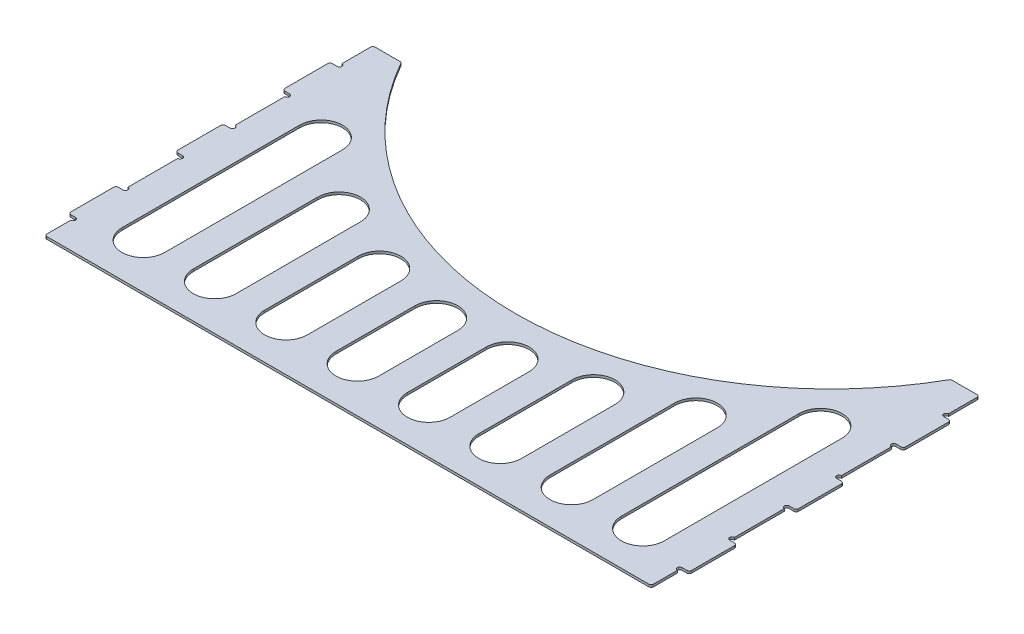
SolidWorks part; units mm, degrees
material "Thornel Mat VMA"
ref_plane "前视基准面" through (0, 0, 0) normal (0, 0, 1) x (1, 0, 0)
ref_plane "上视基准面" through (0, 0, 0) normal (0, 1, 0) x (1, 0, 0)
ref_plane "右视基准面" through (0, 0, 0) normal (1, 0, 0) x (0, 0, -1)
sketch "草图1" plane through (0, 0, 0) normal (0, 1, 0) x (1, 0, 0)
  line L1 (-127.5, -138) -> (127.5, -138)
  line L9 (-127.5, -138) -> (-127.5, 0)
  line L10 (-127.5, 0) -> (127.5, 0)
  line L13 (0, -0.55) -> (0, 0.55) construction
  line L14 (127.5, -138) -> (127.5, 0)
  dimension "D3" = 255
  dimension "D5" = 138
extrude "凸台-拉伸1" add sketch "草图1" along normal blind 1
sketch "草图2" plane through (0, 1, 0) normal (0, 1, 0) x (1, 0, 0)
  line L0 (127.5, 0) -> (-127.5, 0) construction
  line L1 (-115.5, 0) -> (115.5, 0)
  line L2 (-127.5, 0) -> (-127.5, -138) construction
  line L3 (127.5, -138) -> (127.5, 0) construction
  arc A0 (-115.5, 0) -> (115.5, 0) centre (0, 65) ccw
  dimension "D1" = 12
  dimension "D2" = 12
  dimension "D3" = 65
extrude "切除-拉伸1" cut sketch "草图2" against normal through all
sketch "草图5" plane through (0, 1, 0) normal (0, 1, 0) x (1, 0, 0)
  line L0 (-115.5, 0) -> (-127.5, 0) construction
  line L1 (-127.5, -15) -> (-130.5, -15)
  line L2 (-127.5, -15) -> (-127.5, -35)
  line L3 (-127.5, -35) -> (-130.5, -35)
  line L4 (-130.5, -15) -> (-130.5, -35)
  line L5 (-127.5, -60) -> (-130.5, -60)
  line L6 (0, -0.55) -> (0, 0.55) construction
  line L7 (127.5, -35) -> (130.5, -35)
  line L8 (130.5, -15) -> (130.5, -35)
  line L9 (127.5, -15) -> (130.5, -15)
  line L10 (127.5, -15) -> (127.5, -35)
  line L11 (-127.5, 0) -> (-127.5, -138) construction
  line L12 (-127.5, -60) -> (-127.5, -80)
  line L13 (-127.5, -80) -> (-130.5, -80)
  line L14 (-130.5, -60) -> (-130.5, -80)
  line L15 (-127.5, -105) -> (-130.5, -105)
  line L16 (-127.5, -105) -> (-127.5, -125)
  line L17 (-127.5, -125) -> (-130.5, -125)
  line L18 (-130.5, -105) -> (-130.5, -125)
  line L19 (-127.5, 0) -> (-127.5, -138) construction
  line L20 (130.5, -105) -> (130.5, -125)
  line L21 (127.5, -125) -> (130.5, -125)
  line L22 (127.5, -105) -> (127.5, -125)
  line L23 (127.5, -105) -> (130.5, -105)
  line L24 (130.5, -60) -> (130.5, -80)
  line L25 (127.5, -80) -> (130.5, -80)
  line L26 (127.5, -60) -> (127.5, -80)
  line L27 (127.5, -60) -> (130.5, -60)
  dimension "D1" = 3
  dimension "D2" = 20
  dimension "D3" = 15
  dimension "D5" = 25
  dimension "D4" = 3
extrude "凸台-拉伸3" add sketch "草图5" against normal blind 1
sketch "草图6" plane through (0, 1, 0) normal (0, 1, 0) x (1, 0, 0)
  line L0 (-127.5, -35) -> (-127.5, -60) construction
  line L1 (-127.5, -80) -> (-127.5, -105) construction
  line L2 (0, -0.55) -> (0, 0.55) construction
  line L3 (-127.5, 0) -> (-127.5, -15) construction
  line L4 (-127.5, -35) -> (-127.5, -60) construction
  line L5 (-127.5, -125) -> (-127.5, -138) construction
  circle A0 centre (-127.5, -14) radius 1
  circle A1 centre (-127.5, -36) radius 1
  circle A2 centre (127.5, -36) radius 1
  circle A3 centre (127.5, -14) radius 1
  circle A4 centre (-127.5, -59) radius 1
  circle A5 centre (-127.5, -81) radius 1
  circle A6 centre (-127.5, -104) radius 1
  circle A7 centre (-127.5, -126) radius 1
  circle A8 centre (127.5, -126) radius 1
  circle A9 centre (127.5, -104) radius 1
  circle A10 centre (127.5, -81) radius 1
  circle A11 centre (127.5, -59) radius 1
  dimension "D1" = 2
extrude "切除-拉伸3" cut sketch "草图6" against normal through all
sketch "草图7" plane through (0, 1, 0) normal (0, 1, 0) x (1, 0, 0)
  line L0 (-105, -119) -> (-15, -119) construction
  line L3 (-127.5, -138) -> (127.5, -138) construction
  line L9 (-105, -44.2591) -> (-105, -119) construction
  line L10 (-96, -44.2591) -> (-96, -119)
  line L11 (-114, -44.2591) -> (-114, -119)
  line L12 (-75, -66.6721) -> (-75, -119) construction
  line L13 (-66, -66.6721) -> (-66, -119)
  line L14 (-84, -66.6721) -> (-84, -119)
  line L15 (-45, -79.6981) -> (-45, -119) construction
  line L16 (-36, -79.6981) -> (-36, -119)
  line L17 (-54, -79.6981) -> (-54, -119)
  line L260 (-15, -85.7897) -> (-15, -119) construction
  line L261 (-6, -85.7897) -> (-6, -119)
  line L262 (-24, -85.7897) -> (-24, -119)
  line L263 (0, -0.55) -> (0, 0.55) construction
  line L264 (15, -85.7897) -> (15, -119) construction
  line L265 (6, -85.7897) -> (6, -119)
  line L266 (24, -85.7897) -> (24, -119)
  line L289 (45, -79.6981) -> (45, -119) construction
  line L290 (36, -79.6981) -> (36, -119)
  line L291 (54, -79.6981) -> (54, -119)
  line L292 (75, -66.6721) -> (75, -119) construction
  line L293 (66, -66.6721) -> (66, -119)
  line L294 (84, -66.6721) -> (84, -119)
  line L295 (105, -44.2591) -> (105, -119) construction
  line L296 (96, -44.2591) -> (96, -119)
  line L297 (114, -44.2591) -> (114, -119)
  arc A6 (-96, -44.2591) -> (-114, -44.2591) centre (-105, -44.2591) ccw
  arc A7 (-114, -119) -> (-96, -119) centre (-105, -119) ccw
  arc A8 (-66, -66.6721) -> (-84, -66.6721) centre (-75, -66.6721) ccw
  arc A9 (-84, -119) -> (-66, -119) centre (-75, -119) ccw
  arc A10 (-36, -79.6981) -> (-54, -79.6981) centre (-45, -79.6981) ccw
  arc A11 (-54, -119) -> (-36, -119) centre (-45, -119) ccw
  arc A14 (-124.2147, -4.9044) -> (124.2147, -4.9044) centre (0, 65) ccw
  circle A15 centre (0, 65) radius 142.534 construction
  arc A168 (-6, -85.7897) -> (-24, -85.7897) centre (-15, -85.7897) ccw
  arc A171 (-24, -119) -> (-6, -119) centre (-15, -119) ccw
  arc A172 (6, -85.7897) -> (24, -85.7897) centre (15, -85.7897) cw
  arc A173 (24, -119) -> (6, -119) centre (15, -119) cw
  arc A174 (36, -79.6981) -> (54, -79.6981) centre (45, -79.6981) cw
  arc A175 (54, -119) -> (36, -119) centre (45, -119) cw
  arc A176 (66, -66.6721) -> (84, -66.6721) centre (75, -66.6721) cw
  arc A177 (84, -119) -> (66, -119) centre (75, -119) cw
  arc A178 (96, -44.2591) -> (114, -44.2591) centre (105, -44.2591) cw
  arc A179 (114, -119) -> (96, -119) centre (105, -119) cw
  point P7 (-15, -128)
  point P23 (-105, -81.6295)
  point P28 (-75, -92.836)
  point P35 (-45, -99.3491)
  point P44 (-15, -102.3949)
  point P62 (15, -102.3949)
  point P74 (45, -99.3491)
  point P81 (75, -92.836)
  point P88 (105, -81.6295)
  dimension "D2" = 18
  dimension "D4" = 10
  dimension "D5" = 10
  dimension "D10" = 12
  dimension "D11" = 12
  dimension "D12" = 12
  dimension "D3" = 12
extrude "切除-拉伸5" cut sketch "草图7" against normal through all
fillet "圆角1" radius 1 19 edges at (-130.5, 0.5, 60) (-130.5, 0.5, 80) (-130.5, 0.5, 105) (-130.5, 0.5, 125) (-127.5, 0.5, 138) (127.5, 0.5, 138) (130.5, 0.5, 125) (130.5, 0.5, 105) (130.5, 0.5, 80) (130.5, 0.5, 60) (130.5, 0.5, 35) (130.5, 0.5, 15) (127.5, 0.5, 0) (115.5, 0.5, 0) (-115.5, 0.5, 0) (-127.5, 0.5, 0) (-127.5, 0.5, 58) (-130.5, 0.5, 35) (-130.5, 0.5, 15)
